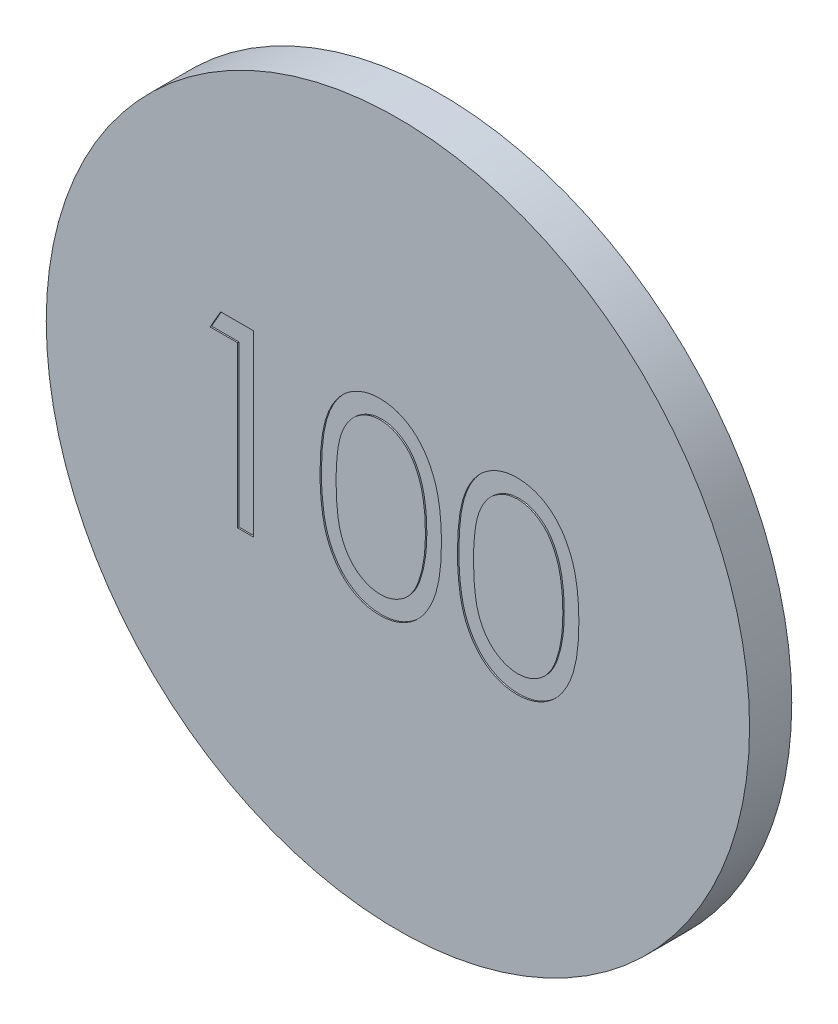
SolidWorks part; units mm, degrees
ref_plane "Front Plane" through (0, 0, 0) normal (1, 0, 0) x (0, 1, 0)
ref_plane "Top Plane" through (0, 0, 0) normal (0, 0, 1) x (0, 1, 0)
ref_plane "Right Plane" through (0, 0, 0) normal (0, 1, 0) x (-1, 0, 0)
sketch "Sketch1" plane through (0, 0, 0) normal (0, 0, 1) x (0, 1, 0)
  circle A0 centre (0, 0) radius 25
  dimension "D1" = 50
extrude "Boss-Extrude1" add sketch "Sketch1" along normal blind 3
sketch "Sketch3" plane through (0, 0, 3) normal (0, 0, 1) x (1, 0, 0)
  line L0 (-11.4811, 26.127) -> (-11.4811, -25.4536) construction
  line L1 (10.4239, 26.127) -> (10.4239, -25.4536) construction
  text T0 "10" font "Lato" height in points 48
extrude "Cut-Extrude1" [suppressed] cut sketch "Sketch3" against normal blind 0.1
sketch "Sketch5" plane through (0, 0, 3) normal (0, 0, 1) x (1, 0, 0)
  text T0 "20" font "Century Gothic" height in points 48
extrude "Cut-Extrude2" [suppressed] cut sketch "Sketch5" against normal blind 0.1
sketch "Sketch7" plane through (0, 0, 3) normal (0, 0, 1) x (1, 0, 0)
  text T0 "50" font "Century Gothic" height in points 48
extrude "Cut-Extrude3" [suppressed] cut sketch "Sketch7" against normal blind 0.1
sketch "Sketch9" plane through (0, 0, 3) normal (0, 0, 1) x (1, 0, 0)
  text T0 "100" font "Century Gothic" height in points 48
extrude "Cut-Extrude4" cut sketch "Sketch9" against normal blind 0.1
